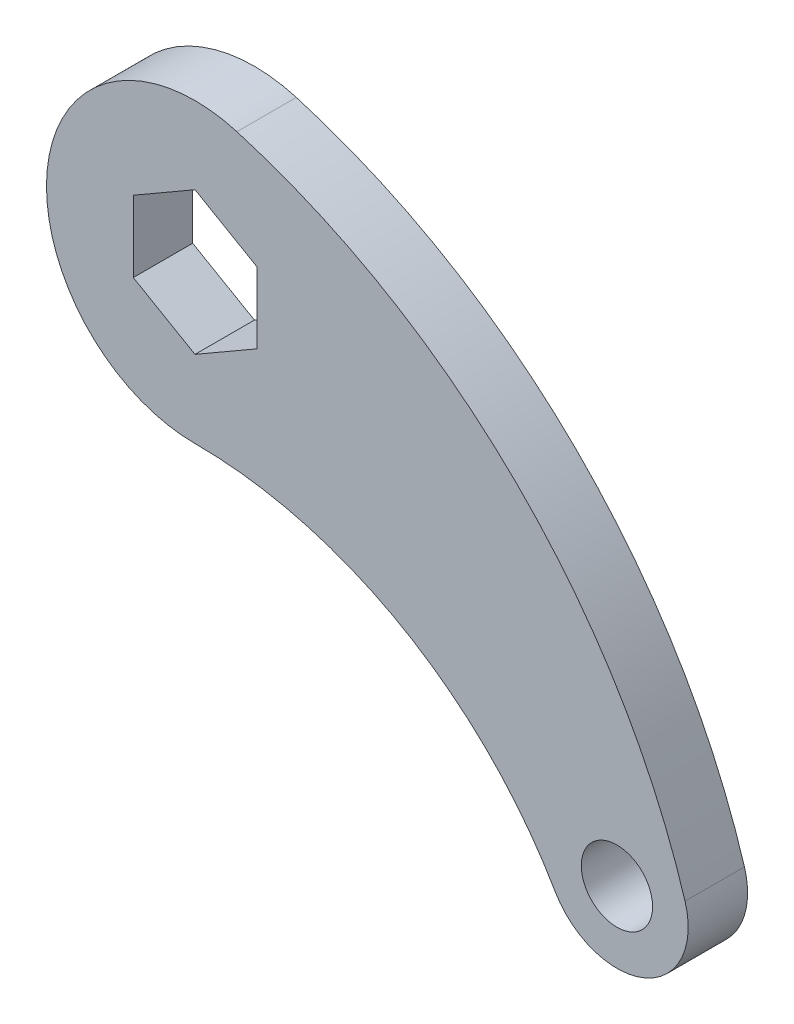
SolidWorks part; units mm, degrees
ref_plane "Front Plane" through (0, 0, 0) normal (0, 0, 1) x (1, 0, 0)
ref_plane "Top Plane" through (0, 0, 0) normal (0, 1, 0) x (1, 0, 0)
ref_plane "Right Plane" through (0, 0, 0) normal (1, 0, 0) x (0, 0, -1)
sketch "Sketch1" plane through (0, 0, 0) normal (0, 0, 1) x (1, 0, 0)
  line L0 (0, 0) -> (0, 95) construction
  line L1 (0, 70) -> (0, 95) construction
  line L3 (0, 83) -> (10.3923, 89)
  line L4 (10.3923, 89) -> (10.3923, 101)
  line L5 (10.3923, 101) -> (0, 107)
  line L6 (0, 107) -> (-10.3923, 101)
  line L7 (-10.3923, 101) -> (-10.3923, 89)
  line L8 (-10.3923, 89) -> (0, 83)
  line L9 (0, 0) -> (60.6218, 35) construction
  line L10 (60.6218, 35) -> (71.0141, 41) construction
  line L11 (0, 95) -> (0, 120) construction
  line L12 (71.0141, 41) -> (81.4064, 47) construction
  arc A1 (60.6218, 35) -> (0, 70) centre (0, 0) ccw
  circle A2 centre (0, 95) radius 25
  circle A3 centre (0, 95) radius 10.3923 construction
  circle A4 centre (71.0141, 41) radius 12
  circle A5 centre (71.0141, 41) radius 6
  arc A6 (82.4813, 44.5359) -> (7.0535, 118.9843) centre (-24.5463, 11.5346) ccw
  point P19 (-21.9834, 37.9691)
  dimension "D1" = 60
extrude "Boss-Extrude1" add sketch "Sketch1" along normal blind 10 contours A2 L8 L7 L6 L5 L4 L3 | A4 A6 A2 A1 | A4 A5
